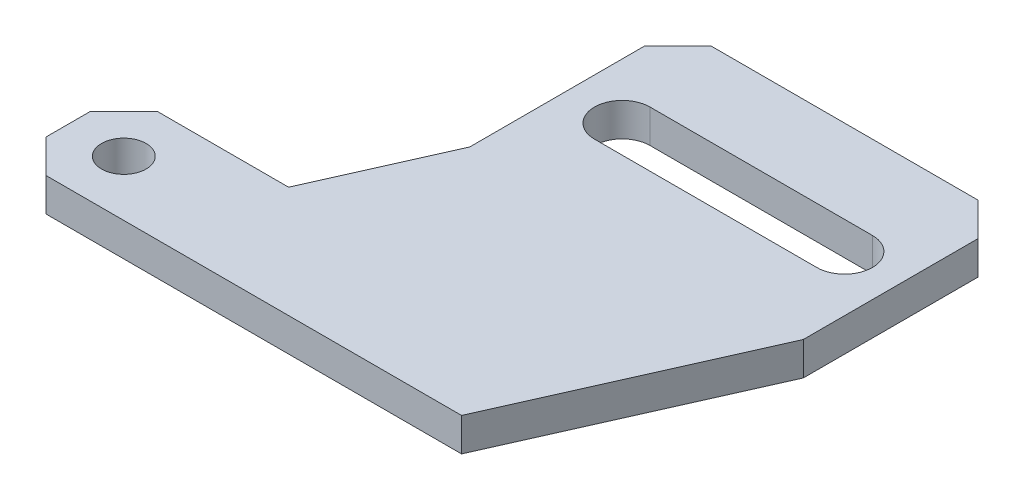
SolidWorks part; units mm, degrees
ref_plane "Alzado" through (0, 0, 0) normal (0, 0, 1) x (1, 0, 0)
ref_plane "Planta" through (0, 0, 0) normal (0, 1, 0) x (1, 0, 0)
ref_plane "Vista lateral" through (0, 0, 0) normal (1, 0, 0) x (0, 0, -1)
sketch "Croquis1" plane through (0, 0, 0) normal (0, 1, 0) x (1, 0, 0)
  line L0 (0, 0) -> (0, 34.7658) construction
  line L2 (-15, 11.288) -> (-15, 30)
  line L3 (-15, 30) -> (15, 30)
  line L4 (15, 11.288) -> (15, 30)
  line L8 (-10, 17.5) -> (10, 17.5)
  line L9 (-10, 22.5) -> (10, 22.5)
  line L13 (-15, 11.288) -> (-20.0124, 0)
  line L14 (-20.0124, 0) -> (-34.8331, 0)
  line L15 (-34.8331, 0) -> (-34.8331, -10)
  line L16 (-34.8331, -10) -> (5.5471, -10)
  line L17 (-15, 11.288) -> (15, 11.288) construction
  line L18 (15, 11.288) -> (5.5471, -10)
  line L19 (-10, 20) -> (10, 20) construction
  arc A0 (-10, 22.5) -> (-10, 17.5) centre (-10, 20) ccw
  arc A1 (10, 17.5) -> (10, 22.5) centre (10, 20) ccw
  circle A2 centre (-29.8331, -5) radius 2
  point P0 (0, 0)
  point P2 (0, 20)
  point P4 (0, 30)
  point P15 (-34.8331, -5)
  dimension "D5" = 5
  dimension "D7" = 10
  dimension "D9" = 5
  dimension "D8" = 4
  dimension "D1" = 30
  dimension "D2" = 20
  dimension "D6" = 10
extrude "Saliente-Extruir1" add sketch "Croquis1" along normal blind 3
chamfer "Chaflán1" distance 3 angle 45 4 edges at (15, 1.5, -30) (-15, 1.5, -30) (-34.8331, 1.5, 10) (-34.8331, 1.5, 0)
